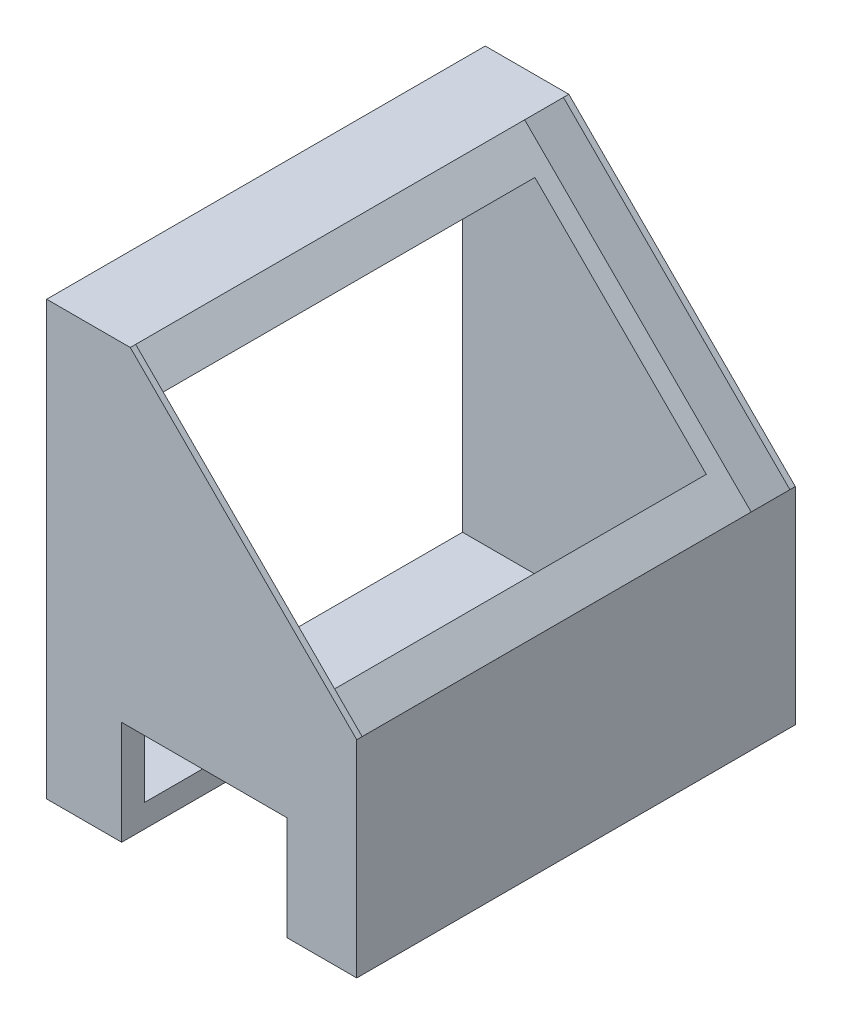
SolidWorks part; units mm, degrees
ref_plane "Front Plane" through (0, 0, 0) normal (0, 0, 1) x (1, 0, 0)
ref_plane "Top Plane" through (0, 0, 0) normal (0, 1, 0) x (1, 0, 0)
ref_plane "Right Plane" through (0, 0, 0) normal (1, 0, 0) x (0, 0, -1)
sketch "Sketch1" plane through (0, 0, 0) normal (0, 0, 1) x (1, 0, 0)
  line L1 (0, 0) -> (150, 0)
  line L2 (0, 0) -> (0, 150)
  line L3 (0, 150) -> (150, 150)
  line L4 (150, 0) -> (150, 150)
  dimension "D2" = 150
extrude "Boss-Extrude2" add sketch "Sketch1" along normal blind 152
chamfer "Chamfer1" distance 78.4889 angle 45 1 edges at (150, 150, 76)
sketch "Sketch4" plane through (110.7556, 110.7556, 0) normal (0.7071, 0.7071, 0) x (0, 0, -1)
  line L0 (-152, -55.5) -> (-152, 55.5) construction
  line L1 (-150.125, 55.5019) -> (-1.875, 55.5019)
  line L2 (-150.125, 55.5019) -> (-150.125, -55.4981)
  line L3 (-150.125, -55.4981) -> (-1.875, -55.4981)
  line L4 (-1.875, 55.5019) -> (-1.875, -55.4981)
  dimension "D1" = 148.25
  dimension "D2" = 111
  dimension "D3" = 1.875
extrude "Cut-Extrude5" cut sketch "Sketch4" against normal blind 19
sketch "Sketch5" plane through (97.3205, 97.3205, 0) normal (0.7071, 0.7071, 0) x (0, 0, -1)
  line L0 (-150.125, -55.4981) -> (-1.875, -55.4981) construction
  line L1 (-144.125, 42.0019) -> (-7.875, 42.0019)
  line L2 (-144.125, 42.0019) -> (-144.125, -41.9981)
  line L3 (-144.125, -41.9981) -> (-7.875, -41.9981)
  line L4 (-7.875, 42.0019) -> (-7.875, -41.9981)
  line L5 (-1.875, -55.4981) -> (-1.875, 55.5) construction
  line L6 (-150.125, 55.5019) -> (-150.125, -55.4981) construction
  line L7 (-1.875, 55.5019) -> (-150.125, 55.5019) construction
  dimension "D1" = 13.5
  dimension "D2" = 6
  dimension "D3" = 6
  dimension "D4" = 13.5
extrude "Cut-Extrude6" cut sketch "Sketch5" against normal blind 81
sketch "Sketch6" plane through (0, 0, 152) normal (0, 0, 1) x (1, 0, 0)
  line L0 (0, 150) -> (71.5111, 150) construction
  line L2 (0, 0) -> (150, 0) construction
  line L4 (42.5367, 0) -> (0, 0)
  line L5 (42.5367, 0) -> (42.5367, 150)
  line L6 (42.5367, 150) -> (0, 150)
  line L7 (0, 0) -> (0, 150)
extrude "Cut-Extrude7" cut sketch "Sketch6" against normal blind 153 and the other way blind 20
sketch "Sketch7" plane through (42.5367, 0, 0) normal (-1, 0, 0) x (0, 0, 1)
  line L0 (152, 0) -> (0, 0) construction
  line L1 (7.875, 37.5531) -> (144.0281, 37.5531)
  line L2 (7.875, 37.5531) -> (7.875, 8)
  line L3 (7.875, 8) -> (144.0281, 8)
  line L4 (144.0281, 37.5531) -> (144.0281, 8)
  dimension "D1" = 8
extrude "Cut-Extrude8" cut sketch "Sketch7" against normal blind 84
sketch "Sketch8" plane through (126.5367, 0, 0) normal (-1, 0, 0) x (0, 0, 1)
  line L0 (144.125, 10.3478) -> (144.125, 67.6234) construction
  line L1 (7.875, 37.5531) -> (144.125, 37.5531)
  line L2 (7.875, 37.5531) -> (7.875, 67.6234)
  line L3 (7.875, 67.6234) -> (144.125, 67.6234)
  line L4 (144.125, 37.5531) -> (144.125, 67.6234)
extrude "Cut-Extrude9" cut sketch "Sketch8" along normal blind 30
sketch "Sketch9" plane through (0, 0, 152) normal (0, 0, 1) x (1, 0, 0)
  line L0 (42.5367, 0) -> (150, 0) construction
  line L1 (68.5367, 0) -> (125.8367, 0)
  line L2 (68.5367, 0) -> (68.5367, 36)
  line L3 (68.5367, 36) -> (125.8367, 36)
  line L4 (125.8367, 0) -> (125.8367, 36)
  line L5 (42.5367, 0) -> (42.5367, 150) construction
  dimension "D1" = 26
  dimension "D2" = 57.3
  dimension "D3" = 36
extrude "Cut-Extrude10" cut sketch "Sketch9" against normal blind 74.6
